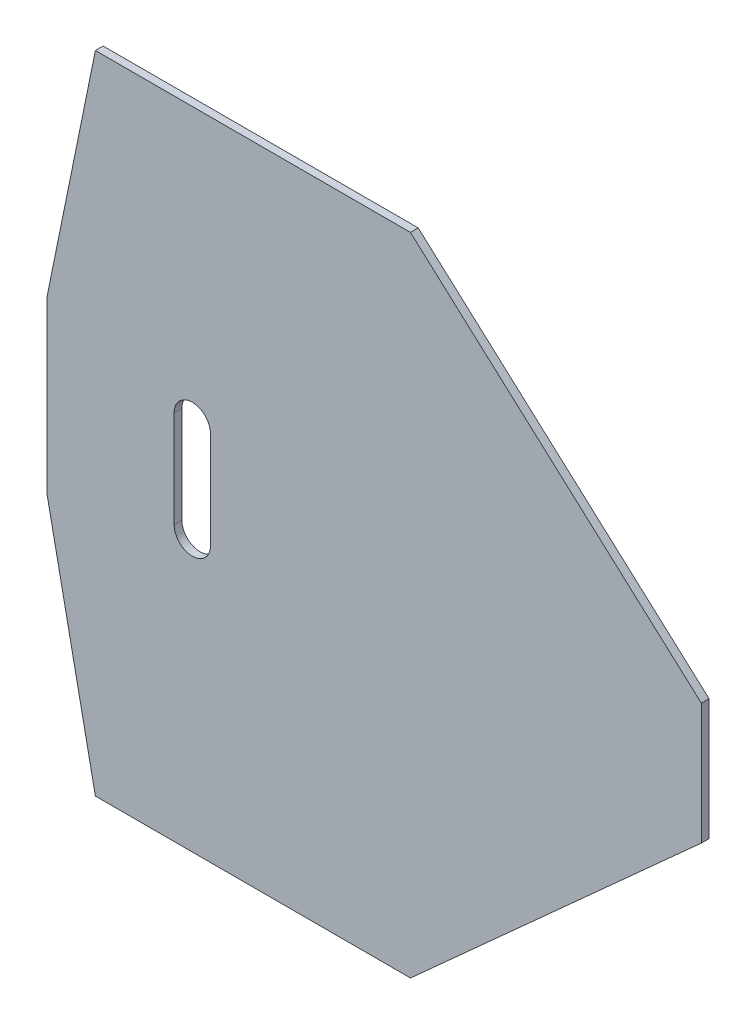
SolidWorks part; units mm, degrees
ref_plane "Спереди" through (0, 0, 0) normal (0, 0, 1) x (1, 0, 0)
ref_plane "Сверху" through (0, 0, 0) normal (0, 1, 0) x (1, 0, 0)
ref_plane "Справа" through (0, 0, 0) normal (1, 0, 0) x (0, 0, -1)
other "Configuration Table"
sketch "Эскиз1" plane through (0, 0, 0) normal (0, 0, 1) x (1, 0, 0)
  line L0 (70, -53.2) -> (-60, -53.2)
  line L1 (-60, -53.2) -> (-80, 45)
  line L2 (-80, 45) -> (-80, 115)
  line L3 (-80, 115) -> (-60, 213.2)
  line L4 (-60, 213.2) -> (70, 213.2)
  line L5 (-80, 80) -> (-50080, 80) construction
  line L6 (190, 55) -> (190, 105)
  line L7 (70, 213.2) -> (190, 105)
  line L8 (190, 55) -> (70, -53.2)
  point P14 (-80, 80)
  point P18 (190, 80)
  dimension "D1" = 50
  dimension "D2" = 270
extrude "Бобышка-Вытянуть1" add sketch "Эскиз1" along normal blind 3.2
sketch "Эскиз2" plane through (0, 0, 3.2) normal (0, 0, 1) x (1, 0, 0)
  line L0 (-20, 60) -> (-20, 100) construction
  line L3 (-80, 80) -> (49920, 80) construction
  line L4 (-80, 115) -> (-80, 45) construction
  line L5 (-27.5, 60) -> (-27.5, 100)
  line L6 (-12.5, 60) -> (-12.5, 100)
  arc A2 (-27.5, 60) -> (-12.5, 60) centre (-20, 60) ccw
  arc A3 (-12.5, 100) -> (-27.5, 100) centre (-20, 100) ccw
  point P2 (-20, 80)
  point P11 (-80, 80)
  dimension "D2" = 40
  dimension "D1" = 60
  dimension "D3" = 15
extrude "Вырез-Вытянуть1" cut sketch "Эскиз2" against normal blind 3.2
